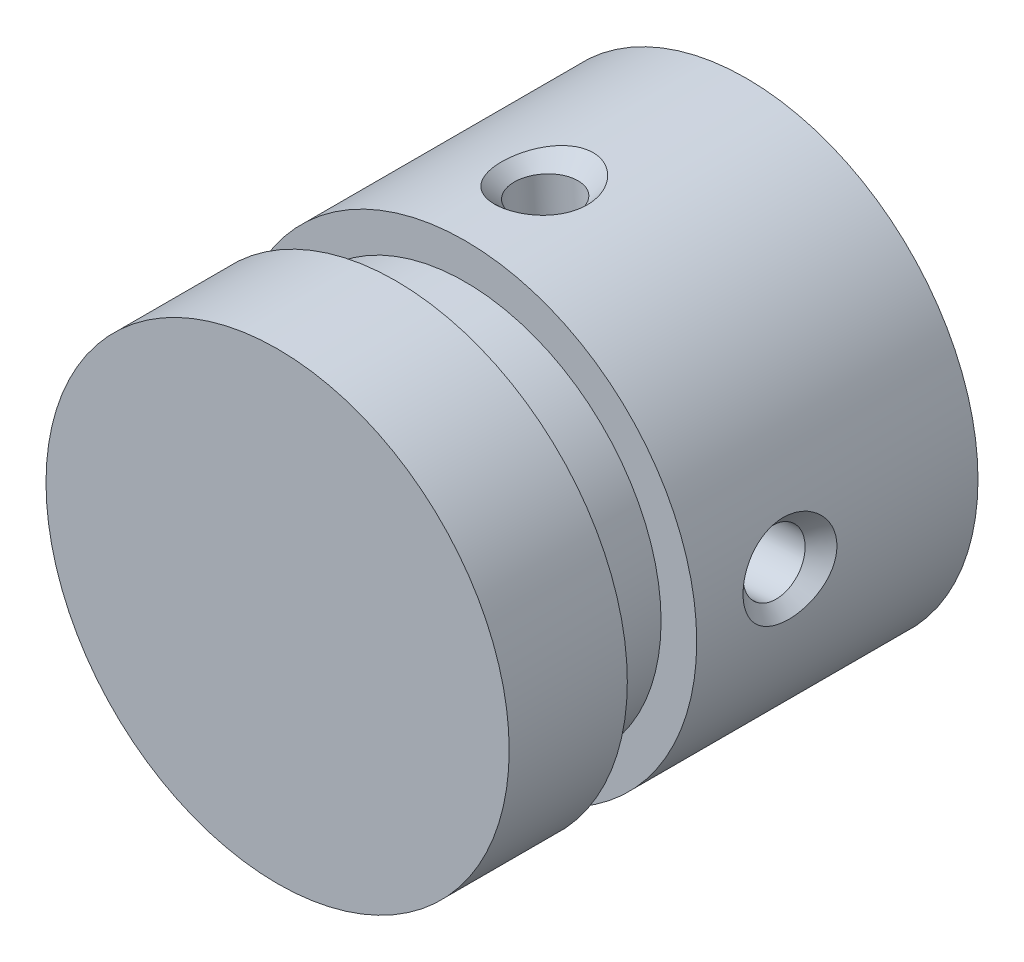
SolidWorks part; units mm, degrees
material "6061-T6 (SS)"
ref_plane "Front Plane" through (0, 0, 0) normal (0, 0, 1) x (1, 0, 0)
ref_plane "Top Plane" through (0, 0, 0) normal (0, 1, 0) x (1, 0, 0)
ref_plane "Right Plane" through (0, 0, 0) normal (1, 0, 0) x (0, 0, -1)
sketch "Sketch1" plane through (0, 0, 0) normal (0, 0, 1) x (1, 0, 0)
  circle A0 centre (0, 0) radius 12.35
  dimension "D1" = 24.7
extrude "Boss-Extrude1" add sketch "Sketch1" along normal blind 25
hole_wizard "M4x0.7 Tapped Hole1" positions "3DSketch1" profile "Sketch2" tap size "M4x0.7" standard "ANSI Metric"
sketch3d "3DSketch1"
  line L0 (-0.7845, 12.3251, 0) -> (-0.7845, 12.3251, 25)
  circle A0 centre (0, 0, 0) radius 12.35 construction
  circle A1 centre (0, 0, 25) radius 12.35 construction
  point P0 (-0.7845, 12.3251, 10)
  point P7 (0, 0, 12.35)
  point P10 (0, 0, 37.35)
  dimension "D1" = 10
sketch "Sketch2" plane through (-0.7845, 12.3251, 10) normal (0, 0, 1) x (-0.998, -0.0635, 0)
  line L0 (0, 0) -> (0, 9.9914)
  line L1 (0, 9.9914) -> (1.65, 9)
  line L2 (1.65, 9) -> (1.65, 0.85)
  line L3 (1.65, 0.85) -> (2.5, 0)
  line L5 (2.5, 0) -> (0, 0)
  line L6 (-1.65, 0.85) -> (-2.5, 0) construction
  line L10 (0, 9.9914) -> (-1.65, 9) construction
  line L11 (0, -6.35) -> (0, 107.95) construction
  dimension "Tap Drill Dia." = 3.3
  dimension "Tap Drill Depth" = 9
  dimension "Near C'Sink Dia." = 5
  dimension "Near C'Sink Angle" = 90
  dimension "Drill Angle" = 118
cosmetic thread "Hole Thread1" parameters "D1"=6, "D2"=4
pattern_circular "CirPattern1" count 4 over 360 about axis through (0, 0, 25) along (0, 0, -1) of "M4x0.7 Tapped Hole1"
cosmetic thread "Hole Thread2" parameters "D1"=6, "D2"=4
cosmetic thread "Hole Thread3" parameters "D1"=6, "D2"=4
cosmetic thread "Hole Thread4" parameters "D1"=6, "D2"=4
ref_plane "Plane1" through (0, 12.35, 0) normal (0, 1, 0) x (1, 0, 0)
sketch "Sketch7" plane through (0, 0, 0) normal (1, 0, 0) x (0, 0, -1)
  line L0 (-15, 12.35) -> (-15, 10.45)
  line L1 (13.585, 12.35) -> (-13.585, 12.35) construction
  line L2 (-15, 10.45) -> (-18.7, 10.45)
  line L3 (-18.7, 10.45) -> (-18.7, 12.35)
  line L4 (0, -12.35) -> (0, 12.35) construction
  line L5 (-18.7, 12.35) -> (-15, 12.35)
  dimension "D1" = 15
  dimension "D2" = 3.7
  dimension "D3" = 1.9
revolve "Cut-Revolve1" cut sketch "Sketch7" angle 360 about axis through (0, 0, 25) along (0, 0, -1)
